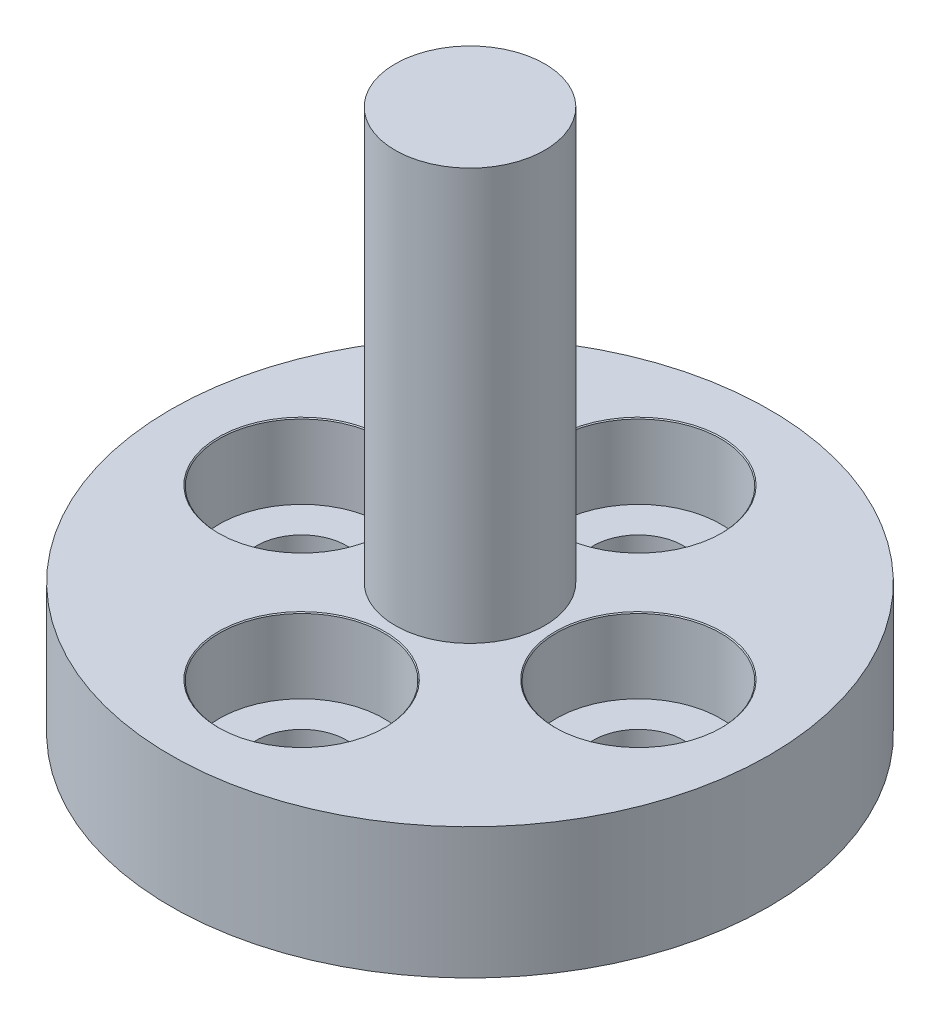
SolidWorks part; units mm, degrees
ref_plane "Front Plane" through (0, 0, 0) normal (0, 0, 1) x (1, 0, 0)
ref_plane "Top Plane" through (0, 0, 0) normal (0, 1, 0) x (1, 0, 0)
ref_plane "Right Plane" through (0, 0, 0) normal (1, 0, 0) x (0, 0, -1)
sketch "Sketch1" plane through (0, 0, 0) normal (0, 0, 1) x (1, 0, 0)
  line L6 (0, 0) -> (8, 0)
  line L7 (8, 0) -> (8, 3.5)
  line L8 (8, 3.5) -> (2, 3.5)
  line L9 (2, 3.5) -> (2, 14.5)
  line L10 (2, 14.5) -> (0, 14.5)
  line L11 (0, 14.5) -> (0, 0)
  dimension "D1" = 8
  dimension "D2" = 14.5
  dimension "D3" = 11
  dimension "D4" = 2
revolve "Revolve1" add sketch "Sketch1" angle 360 about L11
sketch "Sketch2" plane through (0, 3.5, 0) normal (0, 1, 0) x (1, 0, 0)
  circle A0 centre (0, 0) radius 4.5
  dimension "D1" = 9
hole_wizard "CBORE for M2 SHCS1" positions "Sketch3" profile "Sketch4" counterbore size "M2" standard "ANSI Metric" end condition through all
sketch "Sketch3" plane through (0, 3.5, 0) normal (0, 1, 0) x (1, 0, 0)
  circle A0 centre (0, 0) radius 4.5 construction
  point P0 (-4.5, 0)
  point P4 (0, 4.5)
  point P6 (4.5, 0)
  point P8 (0, -4.5)
sketch "Sketch4" plane through (-4.5, 3.5, 0) normal (1, 0, 0) x (0, 0, 1)
  line L0 (0, 0) -> (0, 3.5)
  line L1 (0, 3.5) -> (1.2, 3.5)
  line L3 (1.2, 3.5) -> (1.2, 2)
  line L4 (2.2, 2) -> (1.2, 2)
  line L5 (2.2, 2) -> (2.2, 0.025)
  line L6 (2.2, 0.025) -> (2.225, 0)
  line L7 (2.225, 0) -> (0, 0)
  line L8 (-2.2, 0.025) -> (-2.225, 0) construction
  line L11 (0, -6.35) -> (0, 107.95) construction
  dimension "Thru Hole Dia." = 2.4
  dimension "Thru Hole Depth" = 3.5
  dimension "C'Bore Dia." = 4.4
  dimension "C'Bore Depth" = 2
  dimension "Near C'Sink Dia." = 4.45
  dimension "Near C'Sink Angle" = 90
